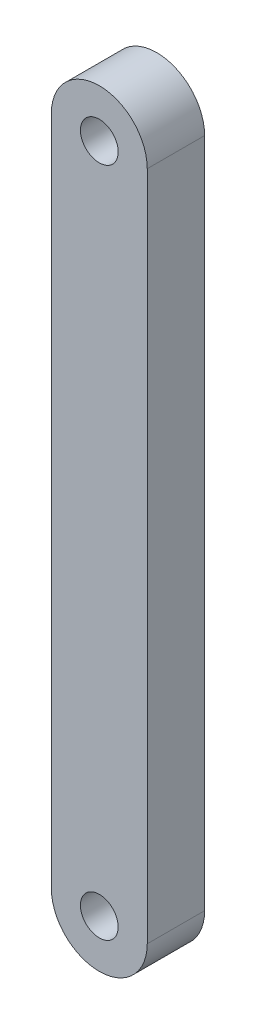
SolidWorks part; units mm, degrees
ref_plane "Front Plane" through (0, 0, 0) normal (0, 0, 1) x (1, 0, 0)
ref_plane "Top Plane" through (0, 0, 0) normal (0, 1, 0) x (1, 0, 0)
ref_plane "Right Plane" through (0, 0, 0) normal (1, 0, 0) x (0, 0, -1)
sketch "Sketch1" plane through (0, 0, 0) normal (0, 0, 1) x (1, 0, 0)
  line L4 (158.8704, 138.7137) -> (158.8704, 129.8237)
  line L5 (160.1404, 129.8237) -> (160.1404, 138.7137)
  arc A4 (158.8704, 129.8237) -> (160.1404, 129.8237) centre (159.5054, 129.8237) ccw
  arc A5 (160.1404, 138.7137) -> (158.8704, 138.7137) centre (159.5054, 138.7137) ccw
  dimension "D3" = 0.635
  dimension "D4" = 0.635
  dimension "D1" = 1.27
  dimension "D2" = 8.89
extrude "Boss-Extrude1" add sketch "Sketch1" along normal blind 0.76
sketch "Sketch2" plane through (0, 0, 0.76) normal (0, 0, 1) x (1, 0, 0)
  circle A0 centre (159.5054, 138.7137) radius 0.25
  circle A1 centre (159.5054, 129.8237) radius 0.25
extrude "Cut-Extrude1" cut sketch "Sketch2" against normal blind 2.76
